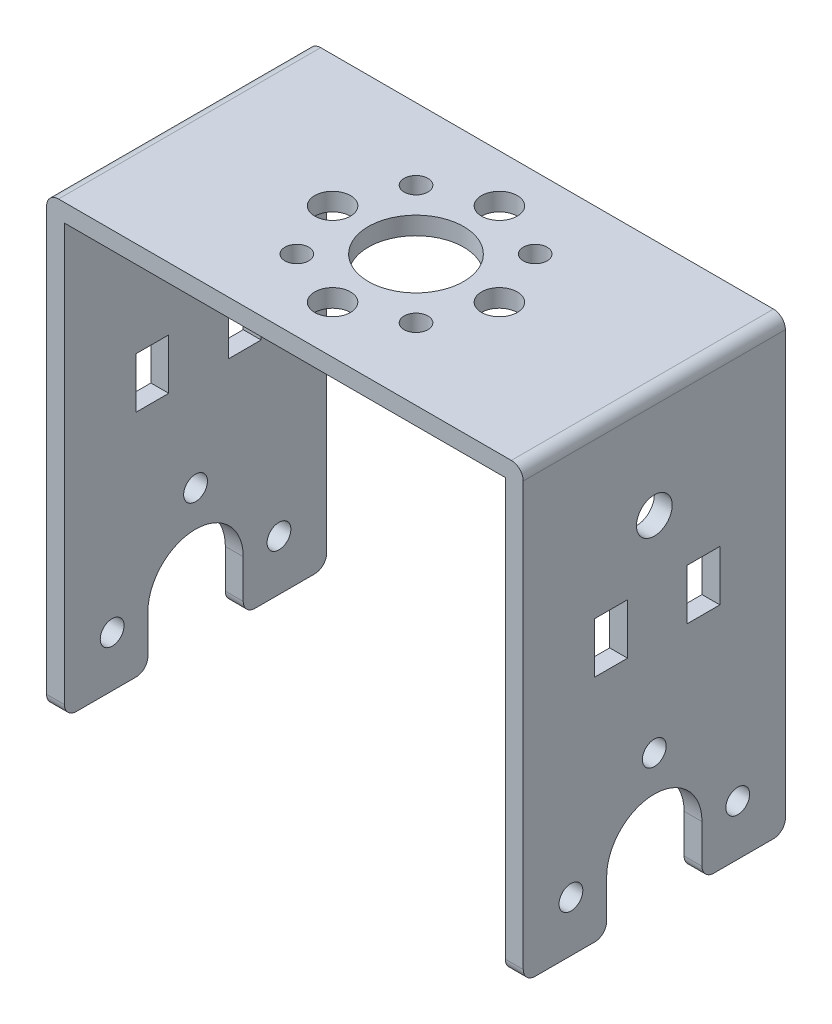
SolidWorks part; units mm, degrees
ref_plane "Front Plane" through (0, 0, 0) normal (0, 0, 1) x (1, 0, 0)
ref_plane "Top Plane" through (0, 0, 0) normal (0, 1, 0) x (1, 0, 0)
ref_plane "Right Plane" through (0, 0, 0) normal (1, 0, 0) x (0, 0, -1)
sketch "Sketch1" plane through (0, 0, 0) normal (0, 1, 0) x (1, 0, 0)
  line L1 (-20, 11) -> (20, 11)
  line L2 (-20, 11) -> (-20, -11)
  line L3 (-20, -11) -> (20, -11)
  line L4 (20, 11) -> (20, -11)
  line L5 (-20, 11) -> (20, -11) construction
  line L6 (-20, -11) -> (20, 11) construction
  circle A0 centre (0, 0) radius 4
  circle A1 centre (0, 7) radius 1.5
  circle A2 centre (7, 0) radius 1.5
  circle A3 centre (0, -7) radius 1.5
  circle A4 centre (-7, 0) radius 1.5
  circle A5 centre (5, 5) radius 1
  circle A6 centre (5, -5) radius 1
  circle A7 centre (-5, -5) radius 1
  circle A8 centre (-5, 5) radius 1
  point P0 (0, 0)
  point P19 (0, 0)
  point P28 (0, 0)
  dimension "D3" = 8
  dimension "D4" = 3
  dimension "D7" = 4
  dimension "D8" = 13
  dimension "D10" = 2
  dimension "D14" = 15
  dimension "D1" = 40
  dimension "D2" = 22
  dimension "D5" = 4
  dimension "D6" = 20
  dimension "D9" = 13
  dimension "D11" = 5
  dimension "D12" = 5
  dimension "D15" = 6
  dimension "D13" = 4
extrude "Boss-Extrude1" add sketch "Sketch1" along normal blind 1.5
sketch "Sketch2" plane through (0, 0, 0) normal (0, -1, 0) x (-1, 0, 0)
  line L0 (20, -11) -> (-20, -11) construction
  line L1 (-20, 11) -> (-18.5, 11)
  line L2 (-20, 11) -> (-20, -11)
  line L3 (-20, -11) -> (-18.5, -11)
  line L4 (-18.5, 11) -> (-18.5, -11)
  dimension "D1" = 1.5
extrude "Boss-Extrude2" add sketch "Sketch2" along normal blind 36
mirror "Mirror1" about plane through (0, 0, 0) normal (1, 0, 0) of "Boss-Extrude2"
fillet "Fillet1" radius 1 2 edges at (20, 1.5, 0) (-20, 1.5, 0)
sketch "Sketch3" plane through (-20, 0, 0) normal (-1, 0, 0) x (0, 0, 1)
  line L0 (-11, 0.5) -> (-11, -36) construction
  line L1 (-11, 1.5) -> (11, 1.5) construction
  line L2 (-4, -31.75) -> (-4, -36)
  line L3 (-5.5, -12.5) -> (-2.75, -12.5)
  line L4 (-5.5, -12.5) -> (-5.5, -16.75)
  line L5 (-5.5, -16.75) -> (-2.75, -16.75)
  line L6 (-2.75, -12.5) -> (-2.75, -16.75)
  line L7 (2.25, -12.5) -> (5, -12.5)
  line L8 (2.25, -12.5) -> (2.25, -16.75)
  line L9 (2.25, -16.75) -> (5, -16.75)
  line L10 (5, -12.5) -> (5, -16.75)
  line L11 (-11, -36) -> (11, -36) construction
  line L12 (4, -31.75) -> (4, -36)
  line L13 (11, 0.5) -> (11, -36) construction
  line L14 (4, -36) -> (-4, -36)
  circle A0 centre (0, -7.5) radius 1.5
  circle A1 centre (0, -24.75) radius 1
  circle A2 centre (-7, -31.75) radius 1
  circle A3 centre (7, -31.75) radius 1
  arc A4 (4, -31.75) -> (-4, -31.75) centre (0, -31.75) ccw
  dimension "D1" = 3
  dimension "D10" = 2
  dimension "D15" = 4
  dimension "D17" = 8
  dimension "D2" = 11
  dimension "D3" = 9
  dimension "D4" = 2.75
  dimension "D5" = 2.75
  dimension "D6" = 5
  dimension "D7" = 5.5
  dimension "D8" = 5
  dimension "D9" = 4.25
  dimension "D11" = 8
  dimension "D12" = 11
  dimension "D13" = 7
  dimension "D14" = 7
  dimension "D16" = 4
  dimension "D18" = 4.25
  dimension "D19" = 7
extrude "Cut-Extrude1" cut sketch "Sketch3" against normal through all
fillet "Fillet2" radius 1 8 edges at (-19.25, -36, 4) (-19.25, -36, 11) (-19.25, -36, -4) (-19.25, -36, -11) (19.25, -36, 11) (19.25, -36, 4) (19.25, -36, -4) (19.25, -36, -11)
